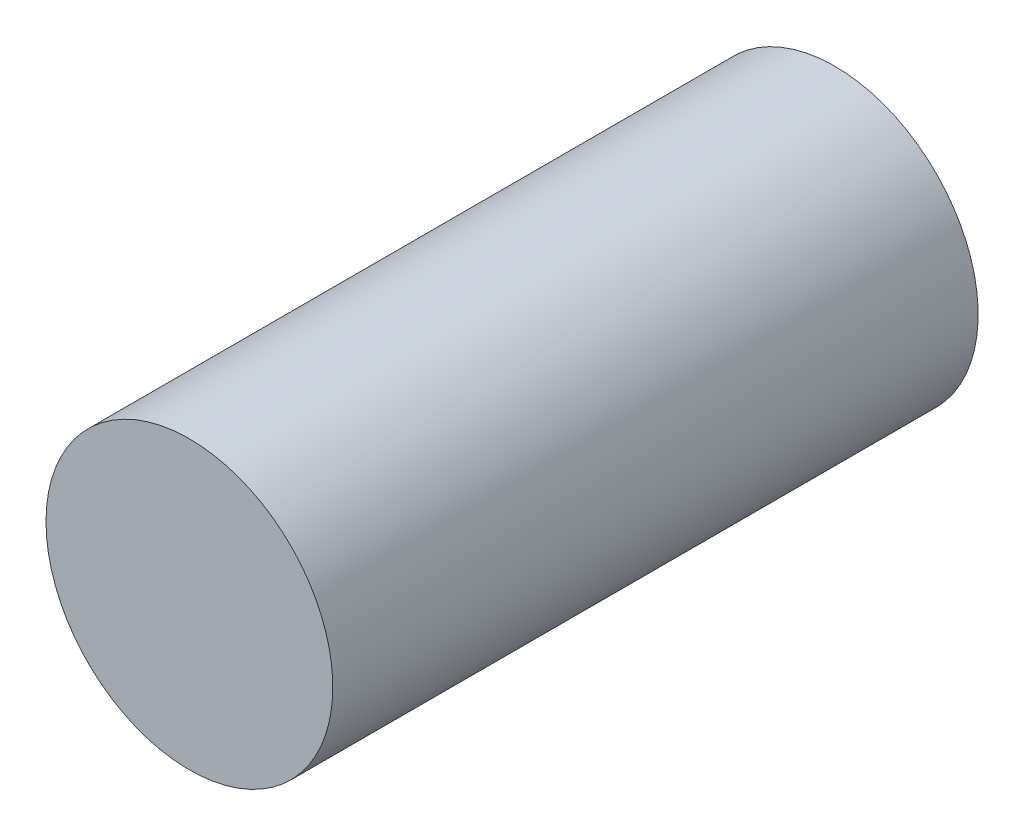
SolidWorks part; units mm, degrees
ref_plane "Front Plane" through (0, 0, 0) normal (0, 0, 1) x (1, 0, 0)
ref_plane "Top Plane" through (0, 0, 0) normal (0, 1, 0) x (1, 0, 0)
ref_plane "Right Plane" through (0, 0, 0) normal (1, 0, 0) x (0, 0, -1)
sketch "Sketch1" plane through (0, 0, 0) normal (0, 0, 1) x (1, 0, 0)
  circle A0 centre (0, 0) radius 10
extrude "Boss-Extrude1" add sketch "Sketch1" along normal blind 45
